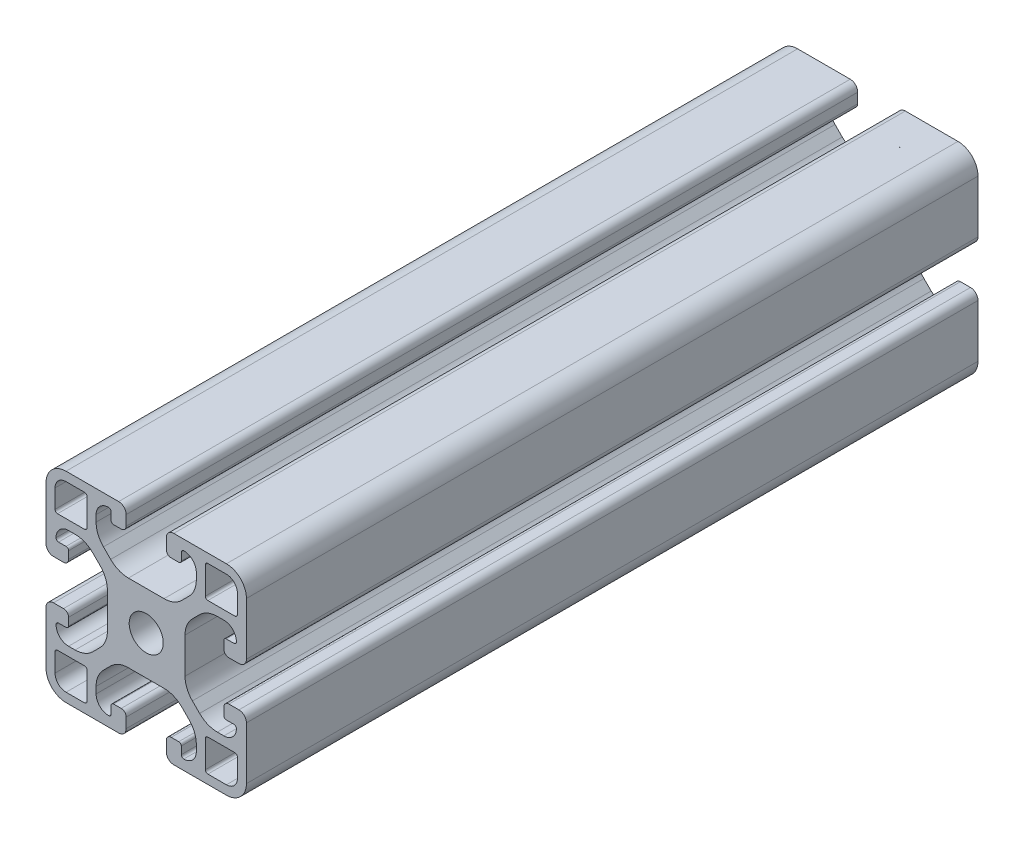
SolidWorks part; units mm, degrees
ref_plane "Plan de face" through (0, 0, 0) normal (0, 0, 1) x (1, 0, 0)
ref_plane "Plan de dessus" through (0, 0, 0) normal (0, 1, 0) x (1, 0, 0)
ref_plane "Plan de droite" through (0, 0, 0) normal (1, 0, 0) x (0, 0, -1)
ref_plane "Plan1" through (0, 0, -30) normal (0, 0, -1) x (-1, 0, 0)
sketch "Esquisse1" plane through (0, 0, -30) normal (0, 0, -1) x (-1, 0, 0)
  line L0 (-4.5, 15) -> (-4.5, 13.5)
  line L1 (-4, 13) -> (-2.5, 13)
  line L2 (-4.5, 10) -> (-5.8076, 10)
  line L3 (-9.3431, 11.4645) -> (-10.7855, 12.9069)
  line L4 (-12.25, 16.4424) -> (-12.25, 23.5576)
  line L5 (-10.7855, 27.0931) -> (-9.3431, 28.5355)
  line L6 (-5.8076, 30) -> (-4.5, 30)
  line L7 (-2.5, 27) -> (-4, 27)
  line L8 (-4.5, 26.5) -> (-4.5, 25)
  line L9 (-3.5, 24) -> (-1.5, 24)
  line L10 (0, 25.5) -> (0, 36)
  line L11 (-4, 40) -> (-14.5, 40)
  line L12 (-16, 38.5) -> (-16, 36.5)
  line L13 (-15, 35.5) -> (-13.5, 35.5)
  line L14 (-13, 36) -> (-13, 37.5)
  line L15 (-10, 35.5) -> (-10, 34.1924)
  line L16 (-11.4645, 30.6569) -> (-12.9069, 29.2145)
  line L17 (-16.4424, 27.75) -> (-23.5576, 27.75)
  line L18 (-27.0931, 29.2145) -> (-28.5355, 30.6569)
  line L19 (-30, 34.1924) -> (-30, 35.5)
  line L20 (-27, 37.5) -> (-27, 36)
  line L21 (-26.5, 35.5) -> (-25, 35.5)
  line L22 (-24, 36.5) -> (-24, 38.5)
  line L23 (-25.5, 40) -> (-36, 40)
  line L24 (-40, 36) -> (-40, 25.5)
  line L25 (-38.5, 24) -> (-36.5, 24)
  line L26 (-35.5, 25) -> (-35.5, 26.5)
  line L27 (-36, 27) -> (-37.5, 27)
  line L28 (-35.5, 30) -> (-34.1924, 30)
  line L29 (-30.6569, 28.5355) -> (-29.2145, 27.0931)
  line L30 (-27.75, 23.5576) -> (-27.75, 16.4424)
  line L31 (-29.2145, 12.9069) -> (-30.6569, 11.4645)
  line L32 (-34.1924, 10) -> (-35.5, 10)
  line L33 (-37.5, 13) -> (-36, 13)
  line L34 (-35.5, 13.5) -> (-35.5, 15)
  line L35 (-36.5, 16) -> (-38.5, 16)
  line L36 (-40, 14.5) -> (-40, 4)
  line L37 (-36, 0) -> (-25.5, 0)
  line L38 (-24, 1.5) -> (-24, 3.5)
  line L39 (-25, 4.5) -> (-26.5, 4.5)
  line L40 (-27, 4) -> (-27, 2.5)
  line L41 (-30, 4.5) -> (-30, 5.8076)
  line L42 (-28.5355, 9.3431) -> (-27.0931, 10.7855)
  line L43 (-23.5576, 12.25) -> (-16.4424, 12.25)
  line L44 (-12.9069, 10.7855) -> (-11.4645, 9.3431)
  line L45 (-10, 5.8076) -> (-10, 4.5)
  line L46 (-13, 2.5) -> (-13, 4)
  line L47 (-13.5, 4.5) -> (-15, 4.5)
  line L48 (-16, 3.5) -> (-16, 1.5)
  line L49 (-14.5, 0) -> (-4, 0)
  line L50 (0, 4) -> (0, 14.5)
  line L51 (-1.5, 16) -> (-3.5, 16)
  line L52 (-4, 1.8) -> (-7.7, 1.8)
  line L53 (-8.2, 2.3) -> (-8.2, 7.7)
  line L54 (-7.7, 8.2) -> (-2.3, 8.2)
  line L55 (-1.8, 7.7) -> (-1.8, 4)
  line L56 (-38.2, 4) -> (-38.2, 7.7)
  line L57 (-37.7, 8.2) -> (-32.3, 8.2)
  line L58 (-31.8, 7.7) -> (-31.8, 2.3)
  line L59 (-32.3, 1.8) -> (-36, 1.8)
  line L60 (-36, 38.2) -> (-32.3, 38.2)
  line L61 (-31.8, 37.7) -> (-31.8, 32.3)
  line L62 (-32.3, 31.8) -> (-37.7, 31.8)
  line L63 (-38.2, 32.3) -> (-38.2, 36)
  line L64 (-1.8, 36) -> (-1.8, 32.3)
  line L65 (-2.3, 31.8) -> (-7.7, 31.8)
  line L66 (-8.2, 32.3) -> (-8.2, 37.7)
  line L67 (-7.7, 38.2) -> (-4, 38.2)
  arc A0 (-4.5, 13.5) -> (-4, 13) centre (-4, 13.5) ccw
  arc A1 (-2.5, 13) -> (-2, 12.5) centre (-2.5, 12.5) cw
  arc A2 (-2, 12.5) -> (-4.5, 10) centre (-4.5, 12.5) cw
  arc A3 (-5.8076, 10) -> (-9.3431, 11.4645) centre (-5.8076, 15) cw
  arc A4 (-10.7855, 12.9069) -> (-12.25, 16.4424) centre (-7.25, 16.4424) cw
  arc A5 (-12.25, 23.5576) -> (-10.7855, 27.0931) centre (-7.25, 23.5576) cw
  arc A6 (-9.3431, 28.5355) -> (-5.8076, 30) centre (-5.8076, 25) cw
  arc A7 (-4.5, 30) -> (-2, 27.5) centre (-4.5, 27.5) cw
  arc A8 (-2, 27.5) -> (-2.5, 27) centre (-2.5, 27.5) cw
  arc A9 (-4, 27) -> (-4.5, 26.5) centre (-4, 26.5) ccw
  arc A10 (-4.5, 25) -> (-3.5, 24) centre (-3.5, 25) ccw
  arc A11 (-1.5, 24) -> (0, 25.5) centre (-1.5, 25.5) ccw
  arc A12 (0, 36) -> (-4, 40) centre (-4, 36) ccw
  arc A13 (-14.5, 40) -> (-16, 38.5) centre (-14.5, 38.5) ccw
  arc A14 (-16, 36.5) -> (-15, 35.5) centre (-15, 36.5) ccw
  arc A15 (-13.5, 35.5) -> (-13, 36) centre (-13.5, 36) ccw
  arc A16 (-13, 37.5) -> (-12.5, 38) centre (-12.5, 37.5) cw
  arc A17 (-12.5, 38) -> (-10, 35.5) centre (-12.5, 35.5) cw
  arc A18 (-10, 34.1924) -> (-11.4645, 30.6569) centre (-15, 34.1924) cw
  arc A19 (-12.9069, 29.2145) -> (-16.4424, 27.75) centre (-16.4424, 32.75) cw
  arc A20 (-23.5576, 27.75) -> (-27.0931, 29.2145) centre (-23.5576, 32.75) cw
  arc A21 (-28.5355, 30.6569) -> (-30, 34.1924) centre (-25, 34.1924) cw
  arc A22 (-30, 35.5) -> (-27.5, 38) centre (-27.5, 35.5) cw
  arc A23 (-27.5, 38) -> (-27, 37.5) centre (-27.5, 37.5) cw
  arc A24 (-27, 36) -> (-26.5, 35.5) centre (-26.5, 36) ccw
  arc A25 (-25, 35.5) -> (-24, 36.5) centre (-25, 36.5) ccw
  arc A26 (-24, 38.5) -> (-25.5, 40) centre (-25.5, 38.5) ccw
  arc A27 (-36, 40) -> (-40, 36) centre (-36, 36) ccw
  arc A28 (-40, 25.5) -> (-38.5, 24) centre (-38.5, 25.5) ccw
  arc A29 (-36.5, 24) -> (-35.5, 25) centre (-36.5, 25) ccw
  arc A30 (-35.5, 26.5) -> (-36, 27) centre (-36, 26.5) ccw
  arc A31 (-37.5, 27) -> (-38, 27.5) centre (-37.5, 27.5) cw
  arc A32 (-38, 27.5) -> (-35.5, 30) centre (-35.5, 27.5) cw
  arc A33 (-34.1924, 30) -> (-30.6569, 28.5355) centre (-34.1924, 25) cw
  arc A34 (-29.2145, 27.0931) -> (-27.75, 23.5576) centre (-32.75, 23.5576) cw
  arc A35 (-27.75, 16.4424) -> (-29.2145, 12.9069) centre (-32.75, 16.4424) cw
  arc A36 (-30.6569, 11.4645) -> (-34.1924, 10) centre (-34.1924, 15) cw
  arc A37 (-35.5, 10) -> (-38, 12.5) centre (-35.5, 12.5) cw
  arc A38 (-38, 12.5) -> (-37.5, 13) centre (-37.5, 12.5) cw
  arc A39 (-36, 13) -> (-35.5, 13.5) centre (-36, 13.5) ccw
  arc A40 (-35.5, 15) -> (-36.5, 16) centre (-36.5, 15) ccw
  arc A41 (-38.5, 16) -> (-40, 14.5) centre (-38.5, 14.5) ccw
  arc A42 (-40, 4) -> (-36, 0) centre (-36, 4) ccw
  arc A43 (-25.5, 0) -> (-24, 1.5) centre (-25.5, 1.5) ccw
  arc A44 (-24, 3.5) -> (-25, 4.5) centre (-25, 3.5) ccw
  arc A45 (-26.5, 4.5) -> (-27, 4) centre (-26.5, 4) ccw
  arc A46 (-27, 2.5) -> (-27.5, 2) centre (-27.5, 2.5) cw
  arc A47 (-27.5, 2) -> (-30, 4.5) centre (-27.5, 4.5) cw
  arc A48 (-30, 5.8076) -> (-28.5355, 9.3431) centre (-25, 5.8076) cw
  arc A49 (-27.0931, 10.7855) -> (-23.5576, 12.25) centre (-23.5576, 7.25) cw
  arc A50 (-16.4424, 12.25) -> (-12.9069, 10.7855) centre (-16.4424, 7.25) cw
  arc A51 (-11.4645, 9.3431) -> (-10, 5.8076) centre (-15, 5.8076) cw
  arc A52 (-10, 4.5) -> (-12.5, 2) centre (-12.5, 4.5) cw
  arc A53 (-12.5, 2) -> (-13, 2.5) centre (-12.5, 2.5) cw
  arc A54 (-13, 4) -> (-13.5, 4.5) centre (-13.5, 4) ccw
  arc A55 (-15, 4.5) -> (-16, 3.5) centre (-15, 3.5) ccw
  arc A56 (-16, 1.5) -> (-14.5, 0) centre (-14.5, 1.5) ccw
  arc A57 (-4, 0) -> (0, 4) centre (-4, 4) ccw
  arc A58 (0, 14.5) -> (-1.5, 16) centre (-1.5, 14.5) ccw
  arc A59 (-3.5, 16) -> (-4.5, 15) centre (-3.5, 15) ccw
  circle A60 centre (-20, 20) radius 3.4
  arc A61 (-1.8, 4) -> (-4, 1.8) centre (-4, 4) cw
  arc A62 (-7.7, 1.8) -> (-8.2, 2.3) centre (-7.7, 2.3) cw
  arc A63 (-8.2, 7.7) -> (-7.7, 8.2) centre (-7.7, 7.7) cw
  arc A64 (-2.3, 8.2) -> (-1.8, 7.7) centre (-2.3, 7.7) cw
  arc A65 (-36, 1.8) -> (-38.2, 4) centre (-36, 4) cw
  arc A66 (-38.2, 7.7) -> (-37.7, 8.2) centre (-37.7, 7.7) cw
  arc A67 (-32.3, 8.2) -> (-31.8, 7.7) centre (-32.3, 7.7) cw
  arc A68 (-31.8, 2.3) -> (-32.3, 1.8) centre (-32.3, 2.3) cw
  arc A69 (-38.2, 36) -> (-36, 38.2) centre (-36, 36) cw
  arc A70 (-32.3, 38.2) -> (-31.8, 37.7) centre (-32.3, 37.7) cw
  arc A71 (-31.8, 32.3) -> (-32.3, 31.8) centre (-32.3, 32.3) cw
  arc A72 (-37.7, 31.8) -> (-38.2, 32.3) centre (-37.7, 32.3) cw
  arc A73 (-4, 38.2) -> (-1.8, 36) centre (-4, 36) cw
  arc A74 (-1.8, 32.3) -> (-2.3, 31.8) centre (-2.3, 32.3) cw
  arc A75 (-7.7, 31.8) -> (-8.2, 32.3) centre (-7.7, 32.3) cw
  arc A76 (-8.2, 37.7) -> (-7.7, 38.2) centre (-7.7, 37.7) cw
extrude "Boss.-Extru.1" add sketch "Esquisse1" against normal blind 146
